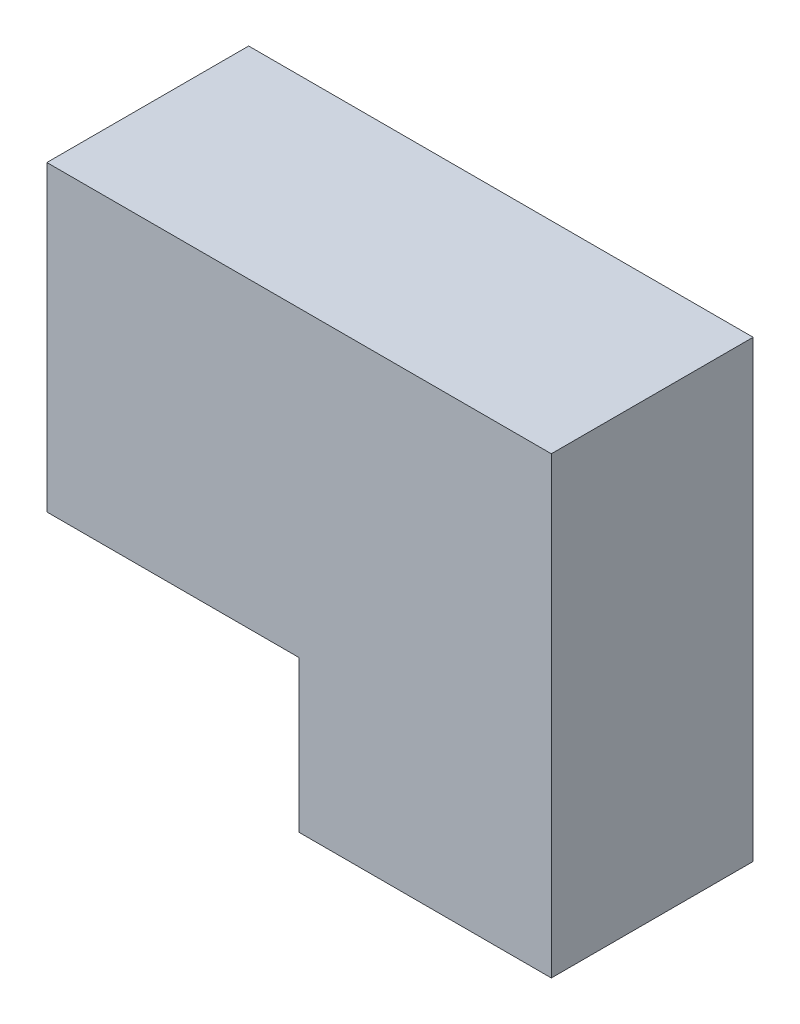
SolidWorks part; units mm, degrees
ref_plane "Front Plane" through (0, 0, 0) normal (0, 0, 1) x (1, 0, 0)
ref_plane "Top Plane" through (0, 0, 0) normal (0, 1, 0) x (1, 0, 0)
ref_plane "Right Plane" through (0, 0, 0) normal (1, 0, 0) x (0, 0, -1)
sketch "Sketch1" plane through (0, 0, 0) normal (0, 0, 1) x (1, 0, 0)
  line L0 (0, 0) -> (0, 3)
  line L1 (0, 3) -> (-5, 3)
  line L2 (-5, 3) -> (-5, 9)
  line L3 (-5, 9) -> (5, 9)
  line L6 (5, 9) -> (5, 0)
  line L7 (5, 0) -> (0, 0)
  dimension "D1" = 5
  dimension "D4" = 6
extrude "Boss-Extrude1" add sketch "Sketch1" along normal blind 4
